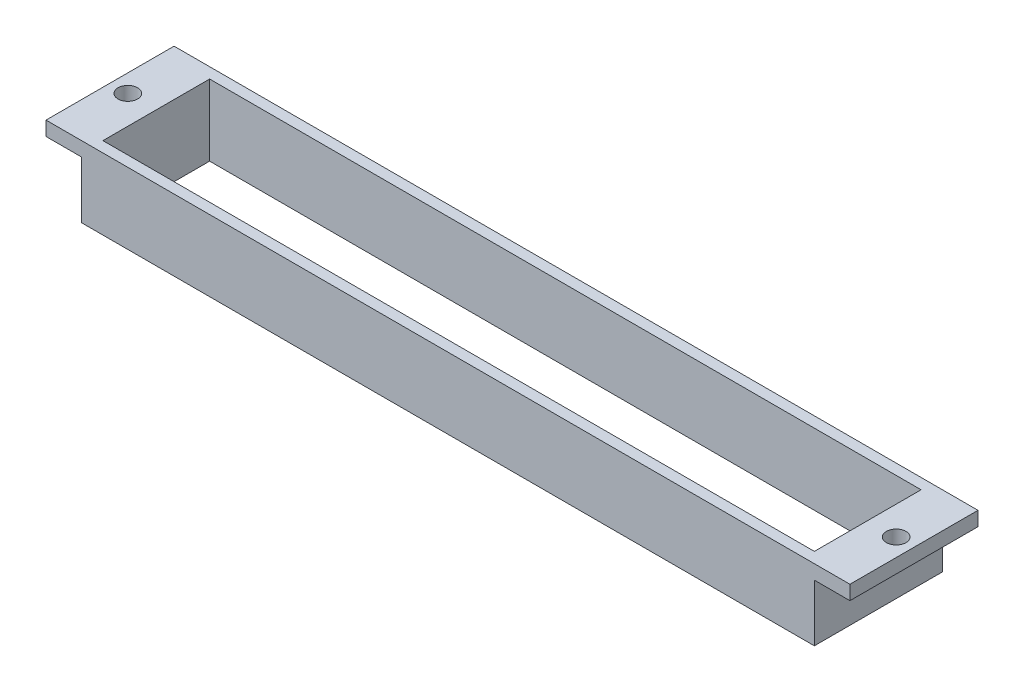
SolidWorks part; units mm, degrees
ref_plane "前视基准面" through (0, 0, 0) normal (0, 0, 1) x (1, 0, 0)
ref_plane "上视基准面" through (0, 0, 0) normal (0, 1, 0) x (1, 0, 0)
ref_plane "右视基准面" through (0, 0, 0) normal (1, 0, 0) x (0, 0, -1)
sketch "草图1" plane through (0, 0, 0) normal (0, 1, 0) x (1, 0, 0)
  line L0 (-103, 18) -> (103, 18)
  line L1 (-100, 15) -> (100, 15)
  line L2 (-100, 15) -> (-100, -15)
  line L3 (-100, -15) -> (100, -15)
  line L4 (100, 15) -> (100, -15)
  line L5 (-100, 15) -> (100, -15) construction
  line L6 (-100, -15) -> (100, 15) construction
  line L7 (103, 18) -> (103, -18)
  line L8 (-103, -18) -> (103, -18)
  line L9 (-103, 18) -> (-103, -18)
  point P0 (0, 0)
  dimension "D1" = 30
  dimension "D2" = 200
  dimension "D3" = 3
extrude "凸台-拉伸1" add sketch "草图1" along normal blind 20
sketch "草图2" plane through (0, 20, 0) normal (0, 1, 0) x (1, 0, 0)
  line L0 (103, 18) -> (-103, 18) construction
  line L1 (-113, 18) -> (-103, 18)
  line L2 (-113, 18) -> (-113, -18)
  line L3 (-113, -18) -> (-103, -18)
  line L4 (113, 18) -> (113, -18)
  line L5 (-113, 18) -> (-103, 16.4071) construction
  line L6 (-113, -18) -> (-103, -16.4071) construction
  line L7 (103, -18) -> (103, 18) construction
  line L8 (-103, 18) -> (-103, -18)
  line L9 (103, 18) -> (103, -18)
  line L10 (103, 18) -> (113, 18)
  line L11 (103, -16.4071) -> (113, -18) construction
  line L12 (103, 16.4071) -> (113, 18) construction
  line L13 (103, -18) -> (113, -18)
  point P0 (0, 0)
  dimension "D1" = 10
extrude "凸台-拉伸2" add sketch "草图2" against normal blind 4
sketch "草图3" plane through (0, 20, 0) normal (0, 1, 0) x (1, 0, 0)
  line L0 (-113, 18) -> (-113, -18) construction
  line L1 (113, -18) -> (113, 18) construction
  circle A0 centre (108, 0) radius 2.75
  circle A1 centre (-108, 0) radius 2.75
  point P4 (0, 0)
  dimension "D1" = 5.5
  dimension "D2" = 5
  dimension "D3" = 5
extrude "切除-拉伸1" cut sketch "草图3" against normal blind 4
